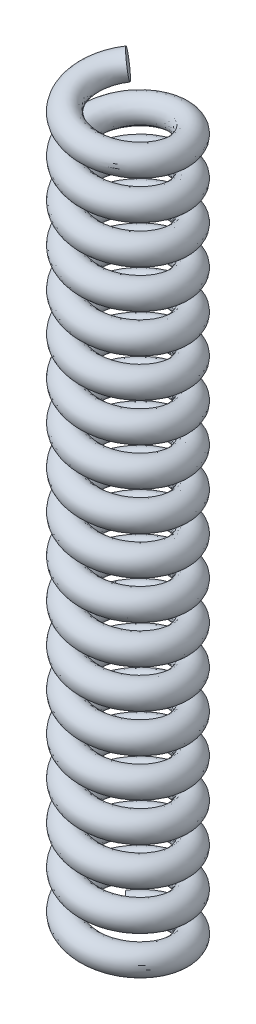
SolidWorks part; units mm, degrees
ref_plane "Front Plane" through (0, 0, 0) normal (0, 0, 1) x (1, 0, 0)
ref_plane "Top Plane" through (0, 0, 0) normal (0, 1, 0) x (1, 0, 0)
ref_plane "Right Plane" through (0, 0, 0) normal (1, 0, 0) x (0, 0, -1)
sketch "Sketch1" plane through (0, 0, 0) normal (0, 1, 0) x (1, 0, 0)
  circle A0 centre (0, 0) radius 3.5
  dimension "D1" = 7
curve "Helix/Spiral1" pitch 3 height 57 turns 19
sweep "Sweep1" add path "Helix/Spiral1" circular profile diameter 2 parameters "D3"=2
